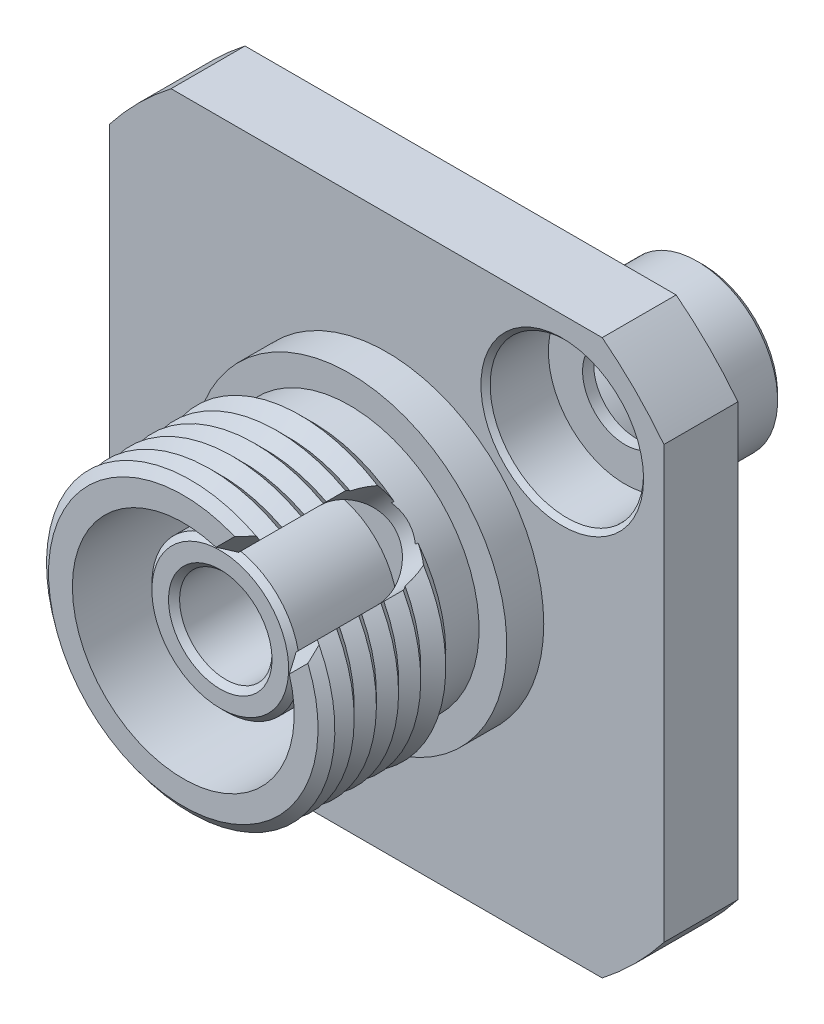
SolidWorks part; units mm, degrees
material "Acier allié inoxydable"
ref_plane "Plan de face" through (0, 0, 0) normal (0, 0, 1) x (1, 0, 0)
ref_plane "Plan de dessus" through (0, 0, 0) normal (0, 1, 0) x (1, 0, 0)
ref_plane "Plan de droite" through (0, 0, 0) normal (1, 0, 0) x (0, 0, -1)
sketch "Esquisse1" plane through (0, 0, 0) normal (0, 0, 1) x (1, 0, 0)
  line L0 (-7.5, 7.5) -> (-7.5, 5.831) construction
  line L1 (-5.831, 7.5) -> (5.831, 7.5)
  line L2 (-7.5, 5.831) -> (-7.5, -5.831)
  line L3 (-5.831, -7.5) -> (5.831, -7.5)
  line L4 (7.5, 5.831) -> (7.5, -5.831)
  line L5 (-7.5, 7.5) -> (7.5, -7.5) construction
  line L6 (-7.5, -7.5) -> (7.5, 7.5) construction
  line L7 (-7.5, -5.831) -> (-7.5, -7.5) construction
  line L8 (-7.5, -7.5) -> (-5.831, -7.5) construction
  line L9 (5.831, -7.5) -> (7.5, -7.5) construction
  line L10 (7.5, -7.5) -> (7.5, -5.831) construction
  line L11 (7.5, 5.831) -> (7.5, 7.5) construction
  line L12 (7.5, 7.5) -> (5.831, 7.5) construction
  line L13 (-5.831, 7.5) -> (-7.5, 7.5) construction
  arc A0 (-7.5, -5.831) -> (-5.831, -7.5) centre (0, 0) ccw
  arc A1 (5.831, -7.5) -> (7.5, -5.831) centre (0, 0) ccw
  arc A2 (7.5, 5.831) -> (5.831, 7.5) centre (0, 0) ccw
  arc A3 (-5.831, 7.5) -> (-7.5, 5.831) centre (0, 0) ccw
  circle A4 centre (0, 0) radius 3
  point P0 (0, 0)
  dimension "D2" = 19
  dimension "D4" = 6
  dimension "D1" = 15
  dimension "D3" = 15
extrude "Boss.-Extru.1" add sketch "Esquisse1" along normal blind 2
sketch "Esquisse3" plane through (0, 0, 0) normal (1, 0, 0) x (0, 0, -1)
  line L2 (-7.5, 3.6453) -> (-7.5, 3)
  line L3 (-3.7, 2) -> (-6.35, 2)
  line L4 (-6.35, 2) -> (-6.5, 1.85)
  line L5 (-6.5, 1.85) -> (-6.5, 1.4)
  line L6 (-6.5, 1.4) -> (-6.35, 1.25)
  line L7 (-6.35, 1.25) -> (6.4, 1.25)
  line L8 (6.4, 1.25) -> (6.55, 1.4)
  line L9 (6.55, 1.4) -> (6.55, 2.025)
  line L10 (6.55, 2.025) -> (6.4, 2.175)
  line L11 (6.4, 2.175) -> (2.5, 2.175)
  line L12 (2.5, 2.175) -> (2.5, 2.85)
  line L13 (2.5, 2.85) -> (2.35, 3)
  line L14 (2.35, 3) -> (-2, 3)
  line L15 (-2, -5.831) -> (-2, 5.831) construction
  line L16 (-2, 3) -> (-2, 4.25)
  line L17 (0, -5.831) -> (0, 5.831) construction
  line L27 (-1, 5.831) -> (-1, -5.831) construction
  line L28 (-2, 5.831) -> (0, 5.831) construction
  line L29 (-2, -5.831) -> (0, -5.831) construction
  line L30 (-4, 3.6) -> (-7.5, 3.6) construction
  line L31 (-4, 3.9) -> (-7.3, 3.9) construction
  line L33 (-7.0771, 3.6) -> (-7.3, 3.9)
  line L34 (-6.7771, 3.9) -> (-7.0771, 3.6)
  line L35 (-6.4771, 3.6) -> (-6.7771, 3.9)
  line L36 (-6.1771, 3.9) -> (-6.4771, 3.6)
  line L37 (-5.8771, 3.6) -> (-6.1771, 3.9)
  line L38 (-5.5771, 3.9) -> (-5.8771, 3.6)
  line L39 (-5.2771, 3.6) -> (-5.5771, 3.9)
  line L40 (-4.9771, 3.9) -> (-5.2771, 3.6)
  line L41 (-4.6771, 3.6) -> (-4.9771, 3.9)
  line L42 (-4.3386, 3.9386) -> (-4.6771, 3.6)
  line L43 (-4, 3.6) -> (-4.3386, 3.9386)
  line L47 (-3.7, 3) -> (-3.7, 2)
  line L48 (-7.5, 3) -> (-3.7, 3)
  line L50 (-7.3, 3.9) -> (-7.5, 3.6453)
  line L51 (-4, 3.5) -> (-4, 3.6)
  line L52 (-3, 3.5) -> (-4, 3.5)
  line L53 (-3, 4.25) -> (-3, 3.5)
  line L54 (-2, 4.25) -> (-3, 4.25)
  dimension "D1" = 4.25
  dimension "D2" = 3
  dimension "D3" = 0.15
  dimension "D4" = 1
  dimension "D5" = 1
  dimension "D6" = 0.15
  dimension "D7" = 3.8
  dimension "D8" = 0.15
  dimension "D9" = 3.5
  dimension "D10" = 45
  dimension "D11" = 45
  dimension "D12" = 45
  dimension "D13" = 45
  dimension "D14" = 2.175
  dimension "D15" = 2.5
  dimension "D16" = 6.55
  dimension "D17" = 1.25
  dimension "D18" = 45
  dimension "D19" = 1
  dimension "D20" = 5.5
  dimension "D21" = 1
ref_axis "Axe1" through (0, 0, -5.875) along (0, 0, 1)
revolve "Révolution1" add sketch "Esquisse3" angle 360 about axis through (0, 0, -5.875) along (0, 0, 1)
hole_wizard "Chambrage pour vis à tête hexagonale M31" positions "Esquisse7" profile "Esquisse6" counterbore size "M3" standard "ISO" end condition through all
sketch "Esquisse7" plane through (0, 0, 2) normal (0, 0, 1) x (1, 0, 0)
  line L1 (4.75, 4.75) -> (-4.75, 4.75) construction
  line L2 (4.75, 4.75) -> (4.75, -4.75) construction
  line L3 (4.75, -4.75) -> (-4.75, -4.75) construction
  line L4 (-4.75, 4.75) -> (-4.75, -4.75) construction
  line L5 (4.75, 4.75) -> (-4.75, -4.75) construction
  line L6 (4.75, -4.75) -> (-4.75, 4.75) construction
  point P0 (4.75, 4.75)
  point P1 (-4.75, -4.75)
  point P4 (0, 0)
  dimension "D1" = 9.5
sketch "Esquisse6" plane through (4.75, 4.75, 2) normal (1, 0, 0) x (0, -1, 0)
  line L0 (0, 0) -> (0, 8.55)
  line L1 (0, 8.55) -> (1.15, 8.55)
  line L3 (1.15, 8.55) -> (1.15, 1.7)
  line L4 (2.075, 1.7) -> (1.15, 1.7)
  line L5 (2.075, 1.7) -> (2.075, 0.125)
  line L6 (2.075, 0.125) -> (2.2, 0)
  line L7 (2.2, 0) -> (0, 0)
  line L8 (-2.075, 0.125) -> (-2.2, 0) construction
  line L11 (0, -6.35) -> (0, 107.95) construction
  dimension "Diamètre du perçage jusqu'au prochain" = 2.3
  dimension "Profondeur du perçage jusqu'au prochain" = 8.55
  dimension "Diamètre du chambrage" = 4.15
  dimension "Profondeur du chambrage" = 1.7
  dimension "Diamètre du fraisage entrant" = 4.4
  dimension "Angle du fraisage entrant" = 90
ref_plane "Plan1" through (6.6655, 6.6655, 0) normal (0.7071, 0.7071, 0) x (-0.7071, 0.7071, 0)
sketch "Esquisse9" plane through (6.6655, 6.6655, 0) normal (0.7071, 0.7071, 0) x (-0.7071, 0.7071, 0)
  line L0 (1.1802, 2) -> (-1.1802, 2) construction
  line L8 (1.1, 7.2) -> (1.1, 5)
  line L9 (2.1256, 8.2256) -> (1.1, 7.2)
  line L10 (-2.1256, 8.2256) -> (2.1256, 8.2256)
  line L11 (-1.1, 7.2) -> (-2.1256, 8.2256)
  line L12 (-1.1, 5) -> (-1.1, 7.2)
  arc A1 (1.1, 5) -> (-1.1, 5) centre (0, 5) cw
  point P0 (0, 2)
  dimension "D1" = 1.1
  dimension "D2" = 3
  dimension "D3" = 2.2
  dimension "D4" = 45
  dimension "D5" = 45
extrude "Enlèv. mat.-Extru.1" cut sketch "Esquisse9" against normal blind 7.3
sketch "Esquisse10" plane through (0, 0, 0) normal (0, 0, -1) x (-1, 0, 0)
  circle A0 centre (0, 5.5) radius 0.75
  dimension "D1" = 1.5
  dimension "D2" = 5.5
extrude "Boss.-Extru.2" add sketch "Esquisse10" along normal blind 1
fillet "Congé1" radius 0.2 1 edges at (-0.75, 5.5, -1)
